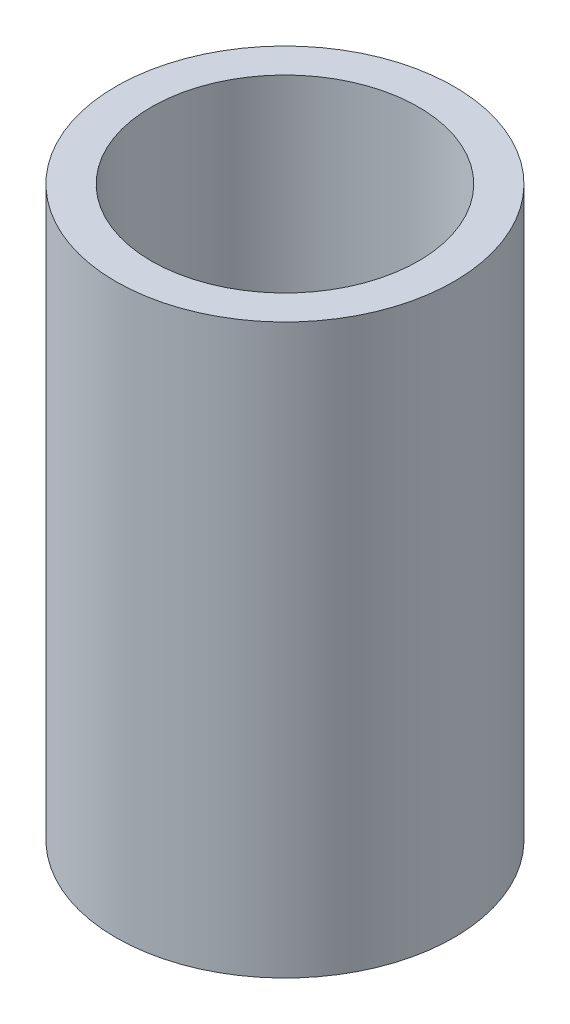
SolidWorks part; units mm, degrees
material "ABS"
ref_plane "Front Plane" through (0, 0, 0) normal (0, 0, 1) x (1, 0, 0)
ref_plane "Top Plane" through (0, 0, 0) normal (0, 1, 0) x (1, 0, 0)
ref_plane "Right Plane" through (0, 0, 0) normal (1, 0, 0) x (0, 0, -1)
sketch "Sketch1" plane through (0, 0, 0) normal (0, 1, 0) x (1, 0, 0)
  circle A0 centre (0, 0) radius 2.3876
  circle A1 centre (0, 0) radius 3.0226
  dimension "D1" = 4.7752
  dimension "D2" = 0.635
extrude "Boss-Extrude1" add sketch "Sketch1" along normal blind 10.16
